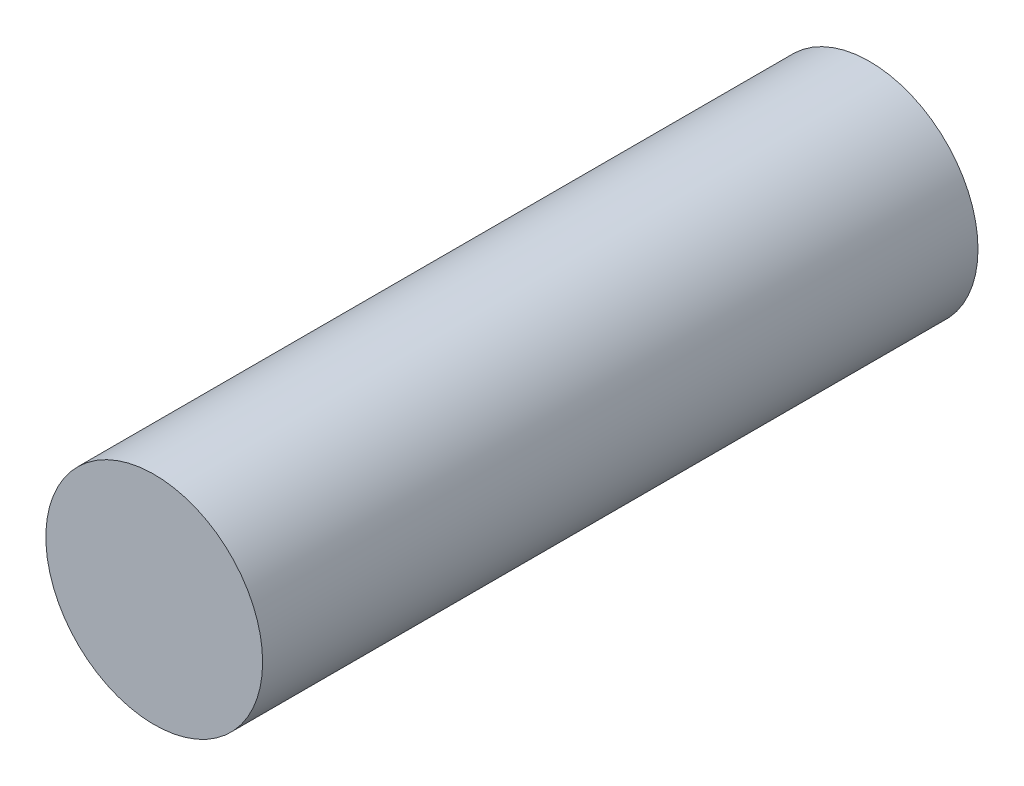
SolidWorks part; units mm, degrees
ref_plane "Front Plane" through (0, 0, 0) normal (0, 0, 1) x (1, 0, 0)
ref_plane "Top Plane" through (0, 0, 0) normal (0, 1, 0) x (1, 0, 0)
ref_plane "Right Plane" through (0, 0, 0) normal (1, 0, 0) x (0, 0, -1)
sketch "Sketch2" plane through (0, 0, 0) normal (0, 0, 1) x (1, 0, 0)
  circle A0 centre (0, 0) radius 10
  dimension "D1" = 20
extrude "Boss-Extrude1" add sketch "Sketch2" along normal blind 66
